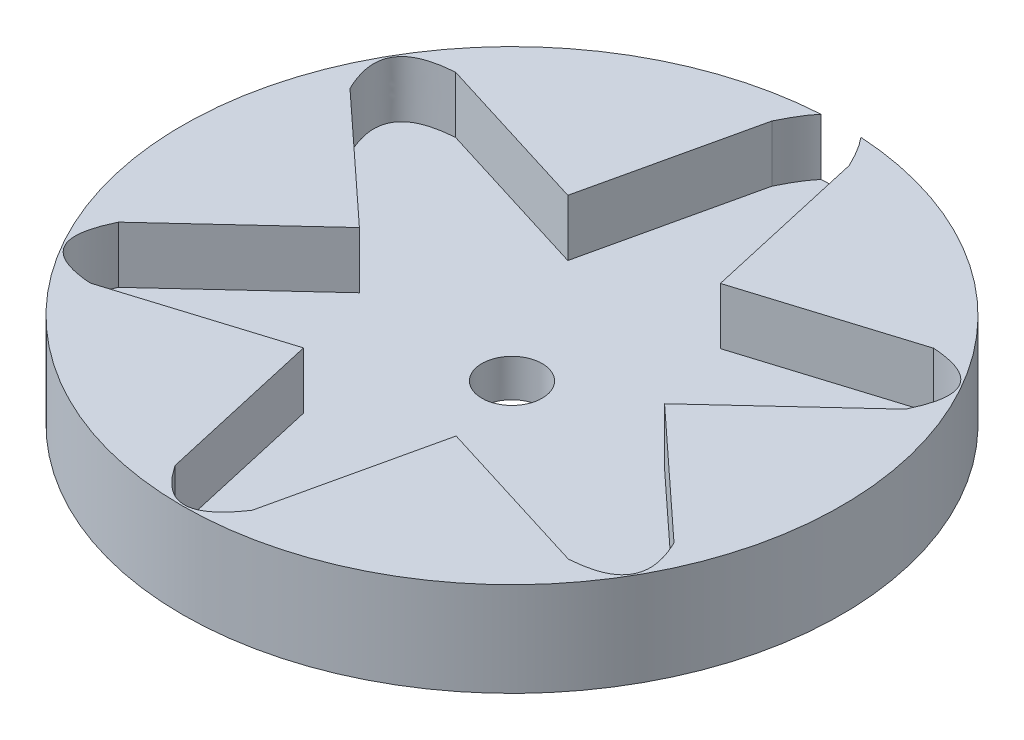
SolidWorks part; units mm, degrees
ref_plane "Front Plane" through (0, 0, 0) normal (0, 0, 1) x (1, 0, 0)
ref_plane "Top Plane" through (0, 0, 0) normal (0, 1, 0) x (1, 0, 0)
ref_plane "Right Plane" through (0, 0, 0) normal (1, 0, 0) x (0, 0, -1)
sketch "Sketch1" plane through (0, 0, 0) normal (0, 1, 0) x (1, 0, 0)
  circle A0 centre (0, 0) radius 17.5
  dimension "D1" = 35
extrude "Boss-Extrude1" add sketch "Sketch1" along normal blind 10
extrude "Cut-Extrude2" cut sketch "Sketch3" against normal blind 3
sketch "Sketch3" plane through (-674.9362, 10, -1288.9633) normal (0, 1, 0) x (1, 0, 0)
  line L0 (672.7905, -1273.0774) -> (670.8112, -1281.8186)
  line L1 (670.8112, -1281.8186) -> (662.2515, -1279.1621)
  line L2 (660.1058, -1282.8786) -> (666.6862, -1288.9633)
  line L3 (666.6862, -1288.9633) -> (660.1058, -1295.048)
  line L4 (662.2515, -1298.7644) -> (670.8112, -1296.108)
  line L5 (670.8112, -1296.108) -> (672.7905, -1304.8491)
  line L6 (677.0818, -1304.8491) -> (679.0612, -1296.108)
  line L7 (679.0612, -1296.108) -> (687.6209, -1298.7644)
  line L8 (689.7666, -1295.048) -> (683.1862, -1288.9633)
  line L9 (683.1862, -1288.9633) -> (689.7666, -1282.8786)
  line L10 (687.6209, -1279.1621) -> (679.0612, -1281.8186)
  line L11 (679.0612, -1281.8186) -> (677.0818, -1273.0774)
  line L12 (659.6988, -1283.1832) -> (665.9497, -1288.9633)
  line L13 (665.9497, -1288.9633) -> (659.6988, -1294.7434)
  line L14 (662.3118, -1299.2692) -> (670.4429, -1296.7458)
  line L15 (670.4429, -1296.7458) -> (672.3232, -1305.0493)
  line L16 (677.5492, -1305.0493) -> (679.4294, -1296.7458)
  line L17 (679.4294, -1296.7458) -> (687.5606, -1299.2692)
  line L18 (690.1736, -1294.7434) -> (683.9226, -1288.9633)
  line L19 (683.9226, -1288.9633) -> (690.1736, -1283.1832)
  line L20 (687.5606, -1278.6573) -> (679.4294, -1281.1808)
  line L21 (679.4294, -1281.1808) -> (677.5576, -1272.9143)
  line L22 (672.3148, -1272.9143) -> (670.4429, -1281.1808)
  line L23 (670.4429, -1281.1808) -> (662.3118, -1278.6573)
  line L24 (660.0244, -1282.9395) -> (666.5389, -1288.9633)
  line L25 (666.5389, -1288.9633) -> (660.0244, -1294.9871)
  line L26 (662.2635, -1298.8654) -> (670.7375, -1296.2356)
  line L27 (670.7375, -1296.2356) -> (672.697, -1304.8892)
  line L28 (677.1753, -1304.8892) -> (679.1348, -1296.2356)
  line L29 (679.1348, -1296.2356) -> (687.6088, -1298.8654)
  line L30 (689.848, -1294.9871) -> (683.3335, -1288.9633)
  line L31 (683.3335, -1288.9633) -> (689.848, -1282.9395)
  line L32 (687.6088, -1279.0612) -> (679.1348, -1281.691)
  line L33 (679.1348, -1281.691) -> (677.177, -1273.0448)
  line L34 (672.6953, -1273.0448) -> (670.7375, -1281.691)
  line L35 (670.7375, -1281.691) -> (662.2635, -1279.0612)
  line L36 (670.8848, -1281.9461) -> (662.2394, -1279.2631)
  line L37 (660.1872, -1282.8177) -> (666.8335, -1288.9633)
  line L38 (666.8335, -1288.9633) -> (660.1872, -1295.1089)
  line L39 (662.2394, -1298.6635) -> (670.8848, -1295.9804)
  line L40 (670.8848, -1295.9804) -> (672.8839, -1304.8091)
  line L41 (676.9884, -1304.8091) -> (678.9875, -1295.9804)
  line L42 (678.9875, -1295.9804) -> (687.6329, -1298.6635)
  line L43 (689.6851, -1295.1089) -> (683.0389, -1288.9633)
  line L44 (683.0389, -1288.9633) -> (689.6851, -1282.8177)
  line L45 (687.6329, -1279.2631) -> (678.9875, -1281.9461)
  line L46 (678.9875, -1281.9461) -> (676.9867, -1273.1101)
  line L47 (672.8856, -1273.1101) -> (670.8848, -1281.9461)
  spline S0 degree 2 poles (672.7905, -1273.0774) (674.9362, -1268.4943) (677.0818, -1273.0774) knots 0 0 0 1 1 1
  spline S1 degree 2 poles (662.2515, -1279.1621) (658.3828, -1279.4062) (660.1058, -1282.8786) knots 0 0 0 1 1 1
  spline S2 degree 2 poles (660.1058, -1295.048) (658.3828, -1298.5204) (662.2515, -1298.7644) knots 0 0 0 1 1 1
  spline S3 degree 2 poles (672.7905, -1304.8491) (674.9362, -1308.0774) (677.0818, -1304.8491) knots 0 0 0 1 1 1
  spline S4 degree 2 poles (687.6209, -1298.7644) (691.4895, -1298.5204) (689.7666, -1295.048) knots 0 0 0 1 1 1
  spline S5 degree 2 poles (689.7666, -1282.8786) (691.4895, -1279.4062) (687.6209, -1279.1621) knots 0 0 0 1 1 1
  spline S12 degree 2 poles (659.6988, -1294.7434) (659.3385, -1295.4464) (659.0765, -1296.4916) (659.0729, -1297.2712) (659.3165, -1297.9813) (659.8096, -1298.5473) (660.4866, -1298.934) (661.5228, -1299.2297) (662.3118, -1299.2692) knots -0.011867 -0.011867 -0.011867 0.180083 0.30805 0.436017 0.563983 0.69195 0.819917 1.011867 1.011867 1.011867
  spline S13 degree 2 poles (672.3232, -1305.0493) (672.7519, -1305.7128) (673.526, -1306.4623) (674.1994, -1306.8553) (674.9362, -1306.9993) (675.6729, -1306.8553) (676.3463, -1306.4623) (677.1205, -1305.7128) (677.5492, -1305.0493) knots -0.011867 -0.011867 -0.011867 0.180083 0.30805 0.436017 0.563983 0.69195 0.819917 1.011867 1.011867 1.011867
  spline S14 degree 2 poles (687.5606, -1299.2692) (688.3495, -1299.2297) (689.3857, -1298.934) (690.0627, -1298.5473) (690.5558, -1297.9813) (690.7995, -1297.2712) (690.7959, -1296.4916) (690.5338, -1295.4464) (690.1736, -1294.7434) knots -0.011867 -0.011867 -0.011867 0.180083 0.30805 0.436017 0.563983 0.69195 0.819917 1.011867 1.011867 1.011867
  spline S15 degree 2 poles (690.1736, -1283.1832) (690.5338, -1282.4802) (690.7959, -1281.435) (690.7995, -1280.6553) (690.5558, -1279.9453) (690.0627, -1279.3793) (689.3857, -1278.9925) (688.3495, -1278.6969) (687.5606, -1278.6573) knots -0.011867 -0.011867 -0.011867 0.180083 0.30805 0.436017 0.563983 0.69195 0.819917 1.011867 1.011867 1.011867
  spline S16 degree 2 poles (677.5576, -1272.9143) (677.1401, -1272.0084) (676.3957, -1270.9987) (675.7324, -1270.4513) (674.9362, -1270.2307) (674.1399, -1270.4513) (673.4766, -1270.9987) (672.7322, -1272.0084) (672.3148, -1272.9143) knots -0.005336 -0.005336 -0.005336 0.184165 0.310499 0.436833 0.563167 0.689501 0.815835 1.005336 1.005336 1.005336
  spline S17 degree 2 poles (662.3118, -1278.6573) (661.5228, -1278.6969) (660.4866, -1278.9925) (659.8096, -1279.3793) (659.3165, -1279.9453) (659.0729, -1280.6553) (659.0765, -1281.435) (659.3385, -1282.4802) (659.6988, -1283.1832) knots -0.011867 -0.011867 -0.011867 0.180083 0.30805 0.436017 0.563983 0.69195 0.819917 1.011867 1.011867 1.011867
  spline S24 degree 2 poles (660.0244, -1294.9871) (659.356, -1296.3079) (659.6, -1297.8176) (660.7854, -1298.7838) (662.2635, -1298.8654) knots -0.002373 -0.002373 -0.002373 0.374407 0.625593 1.002373 1.002373 1.002373
  spline S25 degree 2 poles (672.697, -1304.8892) (673.5067, -1306.1284) (674.9362, -1306.672) (676.3656, -1306.1284) (677.1753, -1304.8892) knots -0.002373 -0.002373 -0.002373 0.374407 0.625593 1.002373 1.002373 1.002373
  spline S26 degree 2 poles (687.6088, -1298.8654) (689.0869, -1298.7838) (690.2724, -1297.8176) (690.5163, -1296.3079) (689.848, -1294.9871) knots -0.002373 -0.002373 -0.002373 0.374407 0.625593 1.002373 1.002373 1.002373
  spline S27 degree 2 poles (689.848, -1282.9395) (690.5163, -1281.6187) (690.2724, -1280.1089) (689.0869, -1279.1428) (687.6088, -1279.0612) knots -0.002373 -0.002373 -0.002373 0.374407 0.625593 1.002373 1.002373 1.002373
  spline S28 degree 2 poles (677.177, -1273.0448) (676.3813, -1271.3068) (674.9362, -1270.5306) (673.491, -1271.3068) (672.6953, -1273.0448) knots -0.001067 -0.001067 -0.001067 0.374733 0.625267 1.001067 1.001067 1.001067
  spline S29 degree 2 poles (662.2635, -1279.0612) (660.7854, -1279.1428) (659.6, -1280.1089) (659.356, -1281.6187) (660.0244, -1282.9395) knots -0.002373 -0.002373 -0.002373 0.374407 0.625593 1.002373 1.002373 1.002373
  spline S36 degree 2 poles (662.2394, -1279.2631) (660.8166, -1279.3644) (659.7866, -1280.2167) (659.5635, -1281.5349) (660.1872, -1282.8177) knots 0.002399 0.002399 0.002399 0.3756 0.6244 0.997601 0.997601 0.997601
  spline S37 degree 2 poles (660.1872, -1295.1089) (659.5635, -1296.3917) (659.7866, -1297.7099) (660.8166, -1298.5622) (662.2394, -1298.6635) knots 0.002399 0.002399 0.002399 0.3756 0.6244 0.997601 0.997601 0.997601
  spline S38 degree 2 poles (672.8839, -1304.8091) (673.683, -1305.9906) (674.9362, -1306.4565) (676.1893, -1305.9906) (676.9884, -1304.8091) knots 0.002399 0.002399 0.002399 0.3756 0.6244 0.997601 0.997601 0.997601
  spline S39 degree 2 poles (687.6329, -1298.6635) (689.0557, -1298.5622) (690.0857, -1297.7099) (690.3089, -1296.3917) (689.6851, -1295.1089) knots 0.002399 0.002399 0.002399 0.3756 0.6244 0.997601 0.997601 0.997601
  spline S40 degree 2 poles (689.6851, -1282.8177) (690.3089, -1281.5349) (690.0857, -1280.2167) (689.0557, -1279.3644) (687.6329, -1279.2631) knots 0.002399 0.002399 0.002399 0.3756 0.6244 0.997601 0.997601 0.997601
  spline S41 degree 2 poles (676.9867, -1273.1101) (676.1733, -1271.411) (674.9362, -1270.7546) (673.699, -1271.411) (672.8856, -1273.1101) knots 0.001074 0.001074 0.001074 0.375269 0.624731 0.998926 0.998926 0.998926
sketch "Sketch4" plane through (0, 0, 0) normal (0, -1, 0) x (1, 0, 0)
  circle A0 centre (0, 0) radius 17.5
extrude "Cut-Extrude3" cut sketch "Sketch4" against normal blind 5
sketch "Sketch5" plane through (0, 7, 0) normal (0, 1, 0) x (1, 0, 0)
  circle A0 centre (0, 0) radius 1.6
extrude "Cut-Extrude4" cut sketch "Sketch5" against normal blind 5
